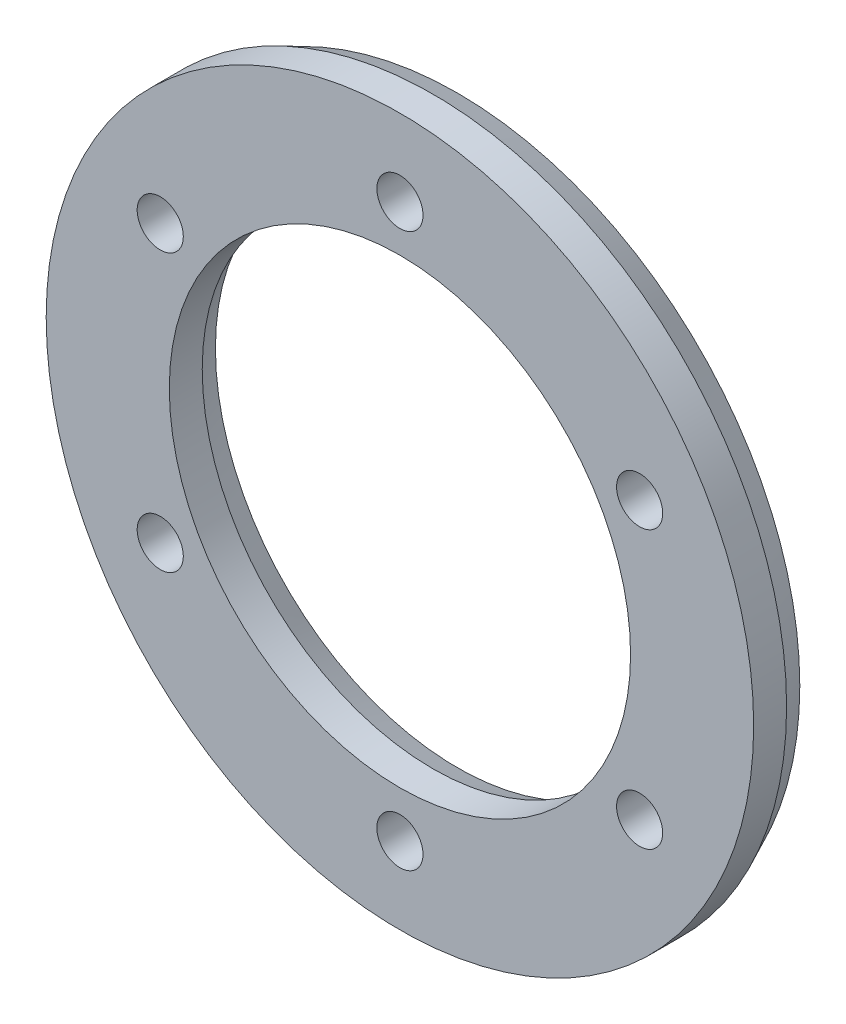
SolidWorks part; units mm, degrees
ref_plane "Front Plane" through (0, 0, 0) normal (0, 0, 1) x (1, 0, 0)
ref_plane "Top Plane" through (0, 0, 0) normal (0, 1, 0) x (1, 0, 0)
ref_plane "Right Plane" through (0, 0, 0) normal (1, 0, 0) x (0, 0, -1)
sketch "Sketch1" plane through (0, 0, 0) normal (0, 0, 1) x (1, 0, 0)
  line L0 (0, 0) -> (0, 24) construction
  circle A3 centre (0, 24) radius 2
  circle A7 centre (0, 0) radius 20
  circle A14 centre (0, 0) radius 24 construction
  circle A20 centre (0, 0) radius 30.675
  circle A21 centre (20.7846, 12) radius 2
  circle A22 centre (20.7846, -12) radius 2
  circle A23 centre (0, -24) radius 2
  circle A24 centre (-20.7846, -12) radius 2
  circle A25 centre (-20.7846, 12) radius 2
  point P16 (0, 0)
  point P18 (0, 0)
  dimension "D1" = 48
  dimension "D2" = 40
  dimension "D3" = 6
  dimension "D5" = 61.35
extrude "Boss-Extrude1" add sketch "Sketch1" along normal blind 5
chamfer "Chamfer6" distance 1 angle 65 2 edges at (30.675, 0, 0) (20, 0, 0)
